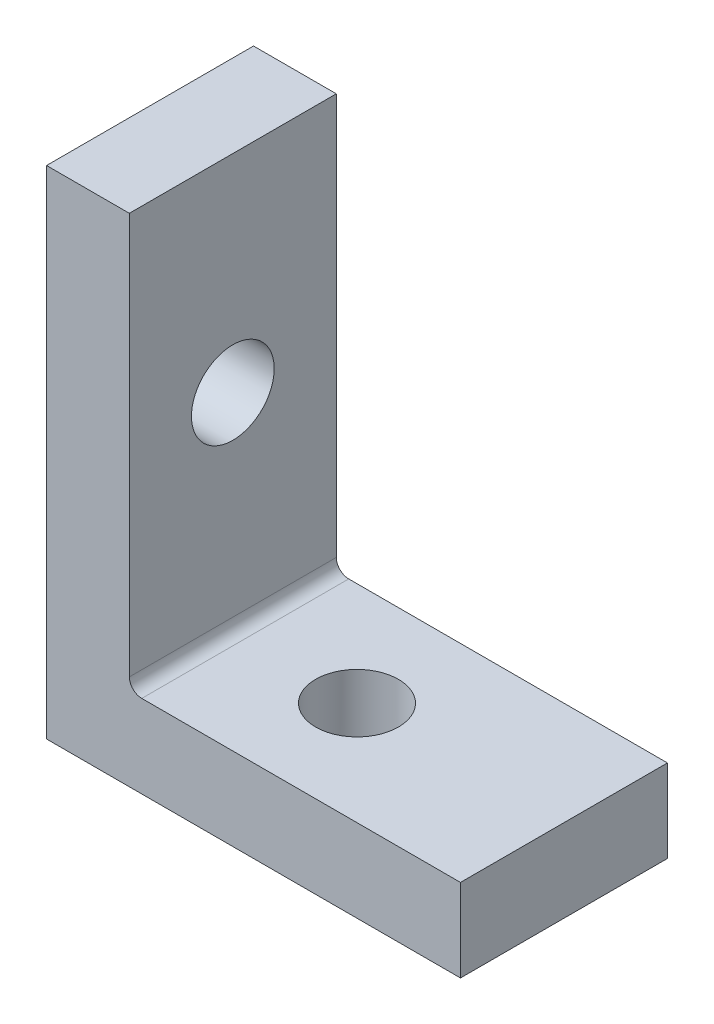
SolidWorks part; units mm, degrees
ref_plane "Front Plane" through (0, 0, 0) normal (0, 0, 1) x (1, 0, 0)
ref_plane "Top Plane" through (0, 0, 0) normal (0, 1, 0) x (1, 0, 0)
ref_plane "Right Plane" through (0, 0, 0) normal (1, 0, 0) x (0, 0, -1)
sketch "Sketch1" plane through (0, 0, 0) normal (0, 1, 0) x (1, 0, 0)
  line L1 (-50, -25) -> (50, -25)
  line L2 (-50, -25) -> (-50, 25)
  line L3 (-50, 25) -> (50, 25)
  line L4 (50, -25) -> (50, 25)
  line L5 (-50, -25) -> (50, 25) construction
  line L6 (-50, 25) -> (50, -25) construction
  point P0 (0, 0)
  dimension "D1" = 100
  dimension "D2" = 50
extrude "Boss-Extrude1" add sketch "Sketch1" along normal blind 20
sketch "Sketch3" plane through (0, 20, 0) normal (0, 1, 0) x (1, 0, 0)
  line L0 (-50, -25) -> (50, -25) construction
  line L1 (-50, 25) -> (-30, 25)
  line L2 (-50, 25) -> (-50, -25)
  line L3 (-50, -25) -> (-30, -25)
  line L4 (-30, 25) -> (-30, -25)
  dimension "D1" = 20
extrude "Boss-Extrude2" add sketch "Sketch3" along normal blind 100
sketch "Sketch4" plane through (-30, 0, 0) normal (1, 0, 0) x (0, 0, -1)
  line L0 (-25, 20) -> (25, 20) construction
  circle A0 centre (0, 70) radius 10
  point P0 (0, 70)
  dimension "D2" = 20
  dimension "D1" = 50
extrude "Cut-Extrude1" cut sketch "Sketch4" against normal blind 100
sketch "Sketch5" plane through (0, 20, 0) normal (0, 1, 0) x (1, 0, 0)
  circle A0 centre (0, 0) radius 10
  dimension "D1" = 20
extrude "Cut-Extrude2" cut sketch "Sketch5" against normal blind 100
fillet "Fillet1" radius 3 1 edges at (-30, 20, 0)
